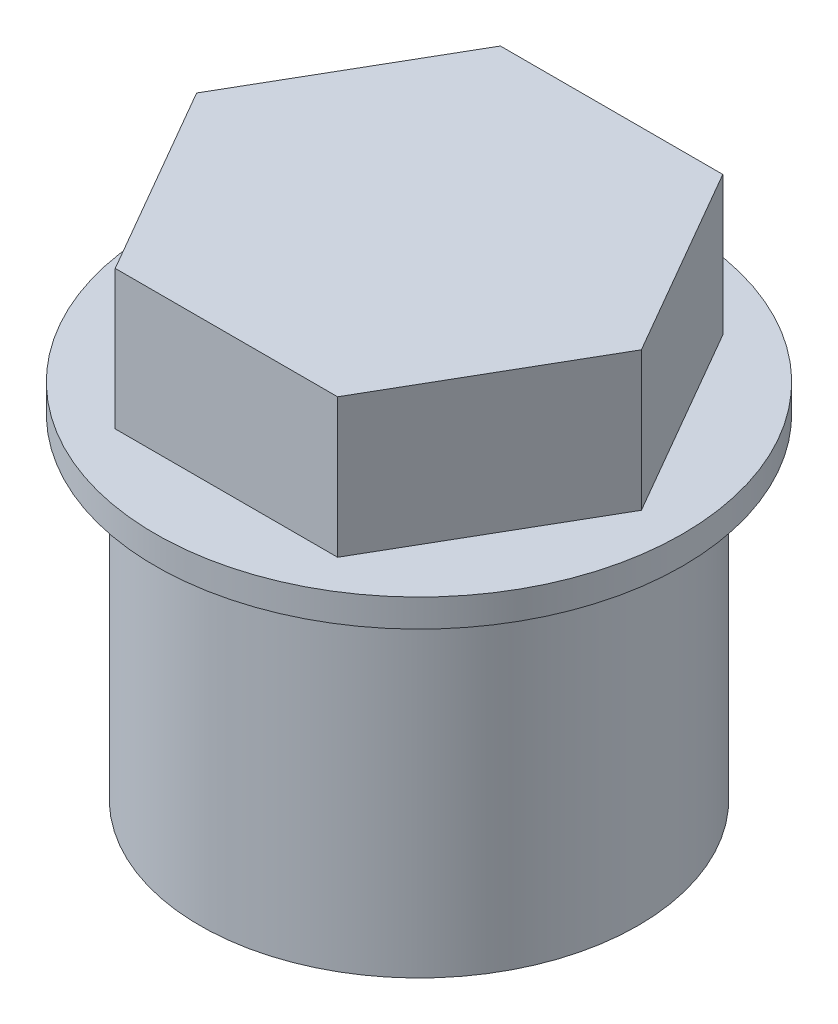
SolidWorks part; units mm, degrees
ref_plane "Front Plane" through (0, 0, 0) normal (0, 0, 1) x (1, 0, 0)
ref_plane "Top Plane" through (0, 0, 0) normal (0, 1, 0) x (1, 0, 0)
ref_plane "Right Plane" through (0, 0, 0) normal (1, 0, 0) x (0, 0, -1)
sketch "Sketch1" plane through (0, 0, 0) normal (0, 0, 1) x (1, 0, 0)
  line L0 (0, 0) -> (0, 15.24)
  line L2 (12.0396, 15.24) -> (12.0396, 16.51)
  line L3 (12.0396, 16.51) -> (10.16, 16.51)
  line L4 (10.16, 16.51) -> (10.16, 22.86)
  line L5 (10.16, 22.86) -> (0, 22.86)
  line L6 (0, 22.86) -> (0, 15.24)
  line L7 (12.0396, 15.24) -> (10.0076, 15.24)
  line L8 (10.0076, 15.24) -> (10.0076, 0)
  line L9 (10.0076, 0) -> (0, 0)
  point P6 (11.0998, 16.51)
  dimension "D1" = 10.0076
  dimension "D2" = 15.24
  dimension "D3" = 1.27
  dimension "D4" = 2.032
  dimension "D5" = 10.16
  dimension "D6" = 6.35
revolve "Revolve1" add sketch "Sketch1" angle 360 about L0
sketch "Sketch2" plane through (0, 22.86, 0) normal (0, 1, 0) x (1, 0, 0)
  line L7 (-5.08, 8.7988) -> (-10.16, 0)
  line L8 (-10.16, 0) -> (-5.08, -8.7988)
  line L9 (-5.08, -8.7988) -> (5.08, -8.7988)
  line L10 (5.08, -8.7988) -> (10.16, 0)
  line L11 (10.16, 0) -> (5.08, 8.7988)
  line L12 (5.08, 8.7988) -> (-5.08, 8.7988)
  circle A0 centre (0, 0) radius 8.7988 construction
  circle A2 centre (0, 0) radius 10.16 construction
  circle A3 centre (0, 0) radius 10.16
  circle A4 centre (0, 0) radius 10.16 construction
  circle M7 centre (0, 0) radius 10.16
extrude "Cut-Extrude1" cut sketch "Sketch2" against normal up to surface (6.35 mm away) contours L8 M7 | L7 M7 | L12 M7 | L11 M7 | L10 M7 | L9 M7 | A3
